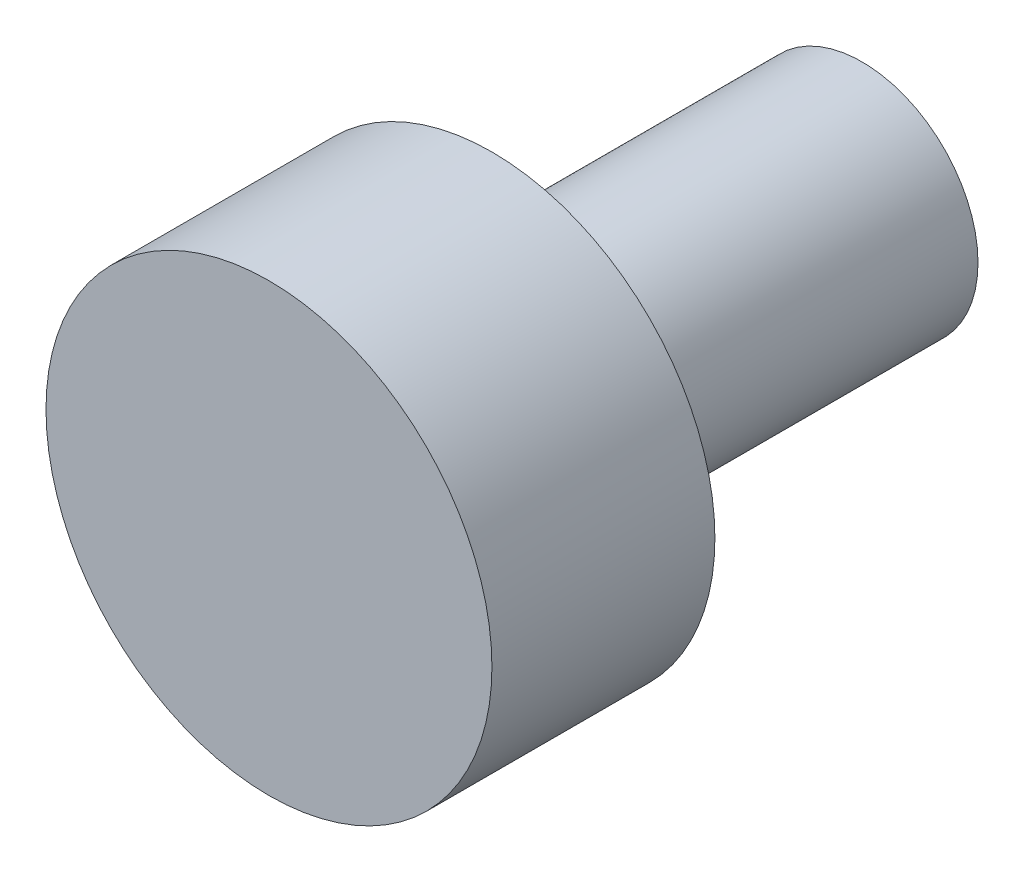
SolidWorks part; units mm, degrees
ref_plane "Plan de face" through (0, 0, 0) normal (0, 0, 1) x (1, 0, 0)
ref_plane "Plan de dessus" through (0, 0, 0) normal (0, 1, 0) x (1, 0, 0)
ref_plane "Plan de droite" through (0, 0, 0) normal (1, 0, 0) x (0, 0, -1)
sketch "Esquisse1" plane through (0, 0, 0) normal (0, 0, 1) x (1, 0, 0)
  circle A0 centre (0, 0) radius 5
  dimension "D1" = 10
extrude "Boss.-Extru.1" add sketch "Esquisse1" along normal blind 5
sketch "Esquisse2" plane through (0, 0, 0) normal (0, 0, -1) x (-1, 0, 0)
  circle A0 centre (0, 0) radius 2.6
  dimension "D1" = 5.2
extrude "Boss.-Extru.2" add sketch "Esquisse2" along normal blind 8.3 contours A0
sketch "Esquisse3" plane through (0, 0, -8.3) normal (0, 0, -1) x (-1, 0, 0)
  circle A0 centre (0, 0) radius 0.9
  dimension "D1" = 1.8
extrude "Enlèv. mat.-Extru.1" cut sketch "Esquisse3" against normal blind 7.5 contours A0
